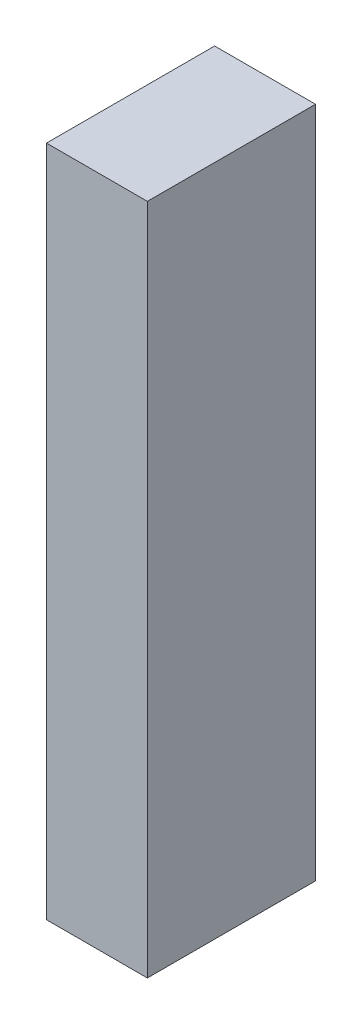
SolidWorks part; units mm, degrees
ref_plane "Front Plane" through (0, 0, 0) normal (0, 0, 1) x (1, 0, 0)
ref_plane "Top Plane" through (0, 0, 0) normal (0, 1, 0) x (1, 0, 0)
ref_plane "Right Plane" through (0, 0, 0) normal (1, 0, 0) x (0, 0, -1)
sketch "Sketch1" plane through (0, 0, 0) normal (0, 1, 0) x (1, 0, 0)
  line L1 (-1.5, 2.5) -> (1.5, 2.5)
  line L2 (-1.5, 2.5) -> (-1.5, -2.5)
  line L3 (-1.5, -2.5) -> (1.5, -2.5)
  line L4 (1.5, 2.5) -> (1.5, -2.5)
  line L5 (-1.5, 2.5) -> (1.5, -2.5) construction
  line L6 (-1.5, -2.5) -> (1.5, 2.5) construction
  point P0 (0, 0)
  dimension "D1" = 3
  dimension "D2" = 5
extrude "Boss-Extrude1" add sketch "Sketch1" along normal blind 20
